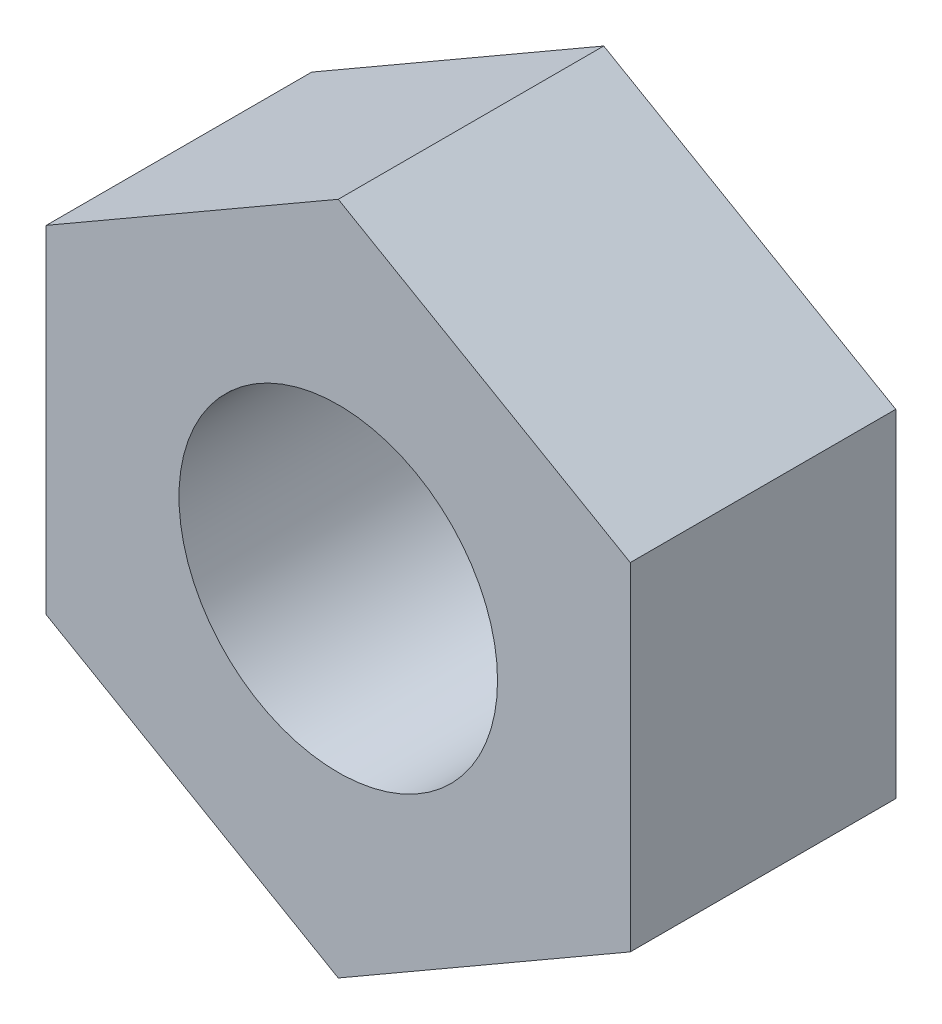
SolidWorks part; units mm, degrees
ref_plane "Front Plane" through (0, 0, 0) normal (0, 0, 1) x (1, 0, 0)
ref_plane "Top Plane" through (0, 0, 0) normal (0, 1, 0) x (1, 0, 0)
ref_plane "Right Plane" through (0, 0, 0) normal (1, 0, 0) x (0, 0, -1)
sketch "Sketch1" plane through (0, 0, 0) normal (0, 0, 1) x (1, 0, 0)
  line L1 (2.75, -1.5877) -> (2.75, 1.5877)
  line L2 (2.75, 1.5877) -> (0, 3.1754)
  line L3 (0, 3.1754) -> (-2.75, 1.5877)
  line L4 (-2.75, 1.5877) -> (-2.75, -1.5877)
  line L5 (-2.75, -1.5877) -> (0, -3.1754)
  line L6 (0, -3.1754) -> (2.75, -1.5877)
  circle A0 centre (0, 0) radius 2.75 construction
  circle A1 centre (0, 0) radius 1.5
  dimension "D2" = 3
  dimension "D1" = 5.5
extrude "Boss-Extrude1" add sketch "Sketch1" along normal blind 2.5
